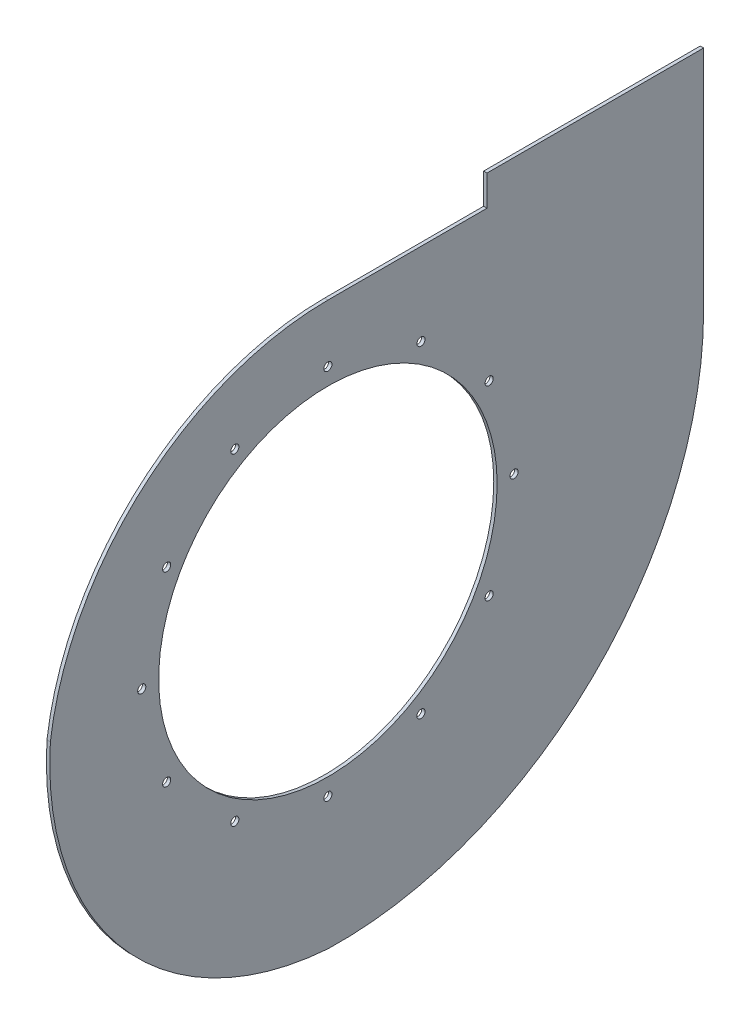
SolidWorks part; units mm, degrees
material "ASTM A36 Steel"
ref_plane "Front Plane" through (0, 0, 0) normal (0, 0, 1) x (1, 0, 0)
ref_plane "Top Plane" through (0, 0, 0) normal (0, 1, 0) x (1, 0, 0)
ref_plane "Right Plane" through (0, 0, 0) normal (1, 0, 0) x (0, 0, -1)
sketch "Sketch1" plane through (0, 0, 0) normal (1, 0, 0) x (0, 0, -1)
  line L0 (-126.9857, 168.7705) -> (193.0143, 168.7705)
  line L1 (-126.9857, 168.7705) -> (-126.9857, 123.7705)
  line L3 (-126.9857, 123.7705) -> (-361.9857, 123.7705)
  line L6 (193.0143, 168.7705) -> (193.0143, -166.6252)
  circle A0 centre (-361.9857, -236.2295) radius 250
  arc A1 (-361.9857, 123.7705) -> (-771.9857, -236.2295) centre (-361.5606, -290.1858) ccw
  arc A2 (-771.9857, -236.2295) -> (-361.9857, -706.2295) centre (-329.7472, -264.2768) ccw
  arc A3 (193.0143, -166.6252) -> (-361.9857, -706.2295) centre (-346.8035, -166.6252) cw
  dimension "D4" = 500
  dimension "D1" = 320
  dimension "D2" = 45
  dimension "D3" = 360
  dimension "D5" = 410
  dimension "D6" = 470
extrude "Boss-Extrude1" add sketch "Sketch1" along normal blind 5
sketch "Sketch2" plane through (5, 0, 0) normal (1, 0, 0) x (0, 0, -1)
  circle A1 centre (-86.9857, -236.2295) radius 6
  dimension "D2" = 12
extrude "Cut-Extrude1" cut sketch "Sketch2" against normal blind 10
pattern_circular "CirPattern1" count 12 every 30 about axis through (0, -236.2295, 361.9857) along (1, 0, 0) of "Cut-Extrude1"
